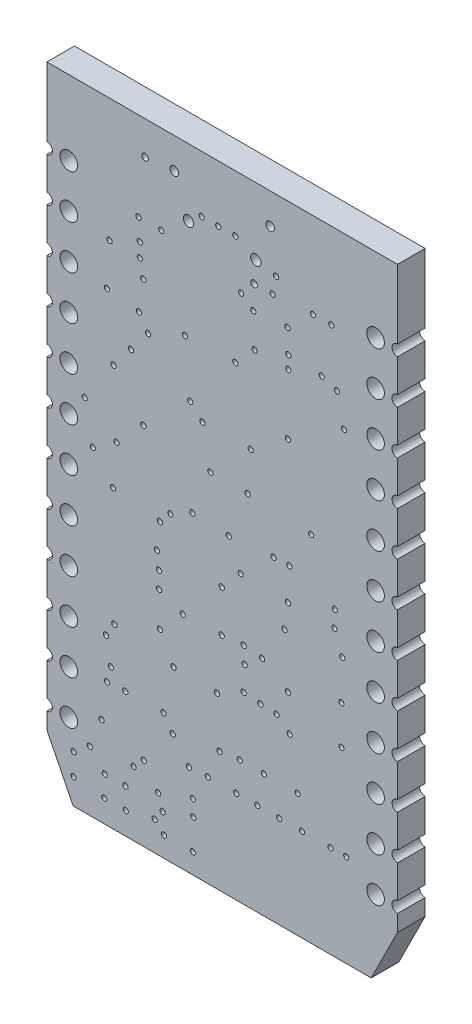
SolidWorks part; units mm, degrees
ref_plane "Front Plane" through (0, 0, 0) normal (0, 0, 1) x (1, 0, 0)
ref_plane "Top Plane" through (0, 0, 0) normal (0, 1, 0) x (1, 0, 0)
ref_plane "Right Plane" through (0, 0, 0) normal (1, 0, 0) x (0, 0, -1)
ref_plane "Dielectric_Layer Layer 1" through (0, 0, 1.6) normal (0, 0, 1) x (1, 0, 0)
sketch "Sketch1" plane through (0, 0, 0) normal (0, 0, 1) x (1, 0, 0)
  line L0 (0, 36.576) -> (0, 3.048)
  line L1 (0, 3.048) -> (1.524, 0)
  line L2 (1.524, 0) -> (18.796, 0)
  line L3 (18.796, 0) -> (20.32, 3.048)
  line L4 (20.32, 3.048) -> (20.32, 36.576)
  line L5 (20.32, 36.576) -> (0, 36.576)
extrude "Board_Outline" add sketch "Sketch1" along normal blind 1.6 separate body
sketch "Sketch2" plane through (0, 0, 0) normal (0, 0, 1) x (1, 0, 0)
  circle A0 centre (12.11, 32.698) radius 0.3
  circle A1 centre (8.21, 32.698) radius 0.3
  circle A2 centre (13.3096, 10.4902) radius 0.1524
  circle A3 centre (17.2212, 26.7462) radius 0.1524
  circle A4 centre (4.8768, 24.5872) radius 0.1524
  circle A5 centre (16.8142, 28.4788) radius 0.1524
  circle A6 centre (9.4742, 20.7264) radius 0.1524
  circle A7 centre (13.9954, 28.1432) radius 0.1524
  circle A8 centre (11.6332, 20.7264) radius 0.1524
  circle A9 centre (10.0076, 6.985) radius 0.1524
  circle A10 centre (13.9954, 28.8798) radius 0.1524
  circle A11 centre (12.0396, 28.1432) radius 0.1524
  circle A12 centre (3.9116, 10.3124) radius 0.1524
  circle A13 centre (5.588, 21.1328) radius 0.1524
  circle A14 centre (3.429, 9.525) radius 0.1524
  circle A15 centre (3.8354, 17.1196) radius 0.1524
  circle A16 centre (11.4046, 10.6426) radius 0.1524
  circle A17 centre (12.3698, 10.541) radius 0.1524
  circle A18 centre (7.874, 12.8016) radius 0.1524
  circle A19 centre (6.5532, 16.7894) radius 0.1524
  circle A20 centre (10.1346, 15.2908) radius 0.1524
  circle A21 centre (11.2268, 16.51) radius 0.1524
  circle A22 centre (14.0462, 18.3134) radius 0.1524
  circle A23 centre (13.1318, 18.288) radius 0.1524
  circle A24 centre (17.1196, 15.2654) radius 0.1524
  circle A25 centre (16.6878, 17.4498) radius 0.1524
  circle A26 centre (9.8552, 9.8298) radius 0.1524
  circle A27 centre (8.4328, 18.161) radius 0.1524
  circle A28 centre (2.4892, 3.4798) radius 0.15
  circle A29 centre (1.5494, 1.4732) radius 0.15
  circle A30 centre (8.4582, 1.1684) radius 0.15
  circle A31 centre (6.2484, 1.7018) radius 0.15
  circle A32 centre (14.5288, 7.1374) radius 0.15
  circle A33 centre (4.5466, 2.5146) radius 0.15
  circle A34 centre (1.5494, 2.7432) radius 0.15
  circle A35 centre (9.3218, 5.3594) radius 0.15
  circle A36 centre (16.4338, 5.3594) radius 0.15
  circle A37 centre (13.462, 5.3594) radius 0.15
  circle A38 centre (10.9728, 5.3594) radius 0.15
  circle A39 centre (12.192, 5.3594) radius 0.15
  circle A40 centre (3.7084, 8.0772) radius 0.15
  circle A41 centre (11.2522, 30.607) radius 0.15
  circle A42 centre (5.3848, 29.4386) radius 0.15
  circle A43 centre (5.3848, 30.2514) radius 0.1524
  circle A44 centre (3.6322, 29.4386) radius 0.1524
  circle A45 centre (8.9662, 33.2994) radius 0.1524
  circle A46 centre (13.2842, 32.4612) radius 0.1524
  circle A47 centre (13.9446, 30.226) radius 0.1524
  circle A48 centre (15.3162, 20.5232) radius 0.15
  circle A49 centre (4.0386, 19.5072) radius 0.15
  circle A50 centre (11.4554, 12.065) radius 0.15
  circle A51 centre (12.4714, 12.8778) radius 0.15
  circle A52 centre (3.4798, 26.9494) radius 0.15
  circle A53 centre (17.0688, 10.7188) radius 0.15
  circle A54 centre (9.017, 23.0124) radius 0.15
  circle A55 centre (17.3482, 5.3594) radius 0.15
  circle A56 centre (3.4798, 7.2136) radius 0.15
  circle A57 centre (14.7828, 5.3594) radius 0.15
  circle A58 centre (3.3528, 2.5146) radius 0.15
  circle A59 centre (11.811, 23.0378) radius 0.15
  circle A60 centre (8.001, 26.8478) radius 0.15
  circle A61 centre (13.97, 24.638) radius 0.15
  circle A62 centre (6.6294, 31.4452) radius 0.15
  circle A63 centre (13.081, 31.4706) radius 0.1524
  circle A64 centre (11.176, 7.1374) radius 0.15
  circle A65 centre (7.1628, 17.4752) radius 0.15
  circle A66 centre (2.1844, 20.828) radius 0.15
  circle A67 centre (17.0688, 12.954) radius 0.15
  circle A68 centre (11.9634, 30.0736) radius 0.15
  circle A69 centre (8.4582, 3.8354) radius 0.15
  circle A70 centre (4.572, 1.2954) radius 0.15
  circle A71 centre (6.7818, 1.1684) radius 0.15
  circle A72 centre (3.3274, 1.2954) radius 0.15
  circle A73 centre (5.0292, 3.7338) radius 0.15
  circle A74 centre (6.7056, 2.3114) radius 0.15
  circle A75 centre (12.573, 7.1374) radius 0.15
  circle A76 centre (8.4836, 2.921) radius 0.15
  circle A77 centre (5.6134, 4.3434) radius 0.15
  circle A78 centre (6.4516, 3.1242) radius 0.15
  circle A79 centre (3.175, 5.1562) radius 0.15
  circle A80 centre (8.2296, 5.3086) radius 0.15
  circle A81 centre (6.7564, 7.2898) radius 0.15
  circle A82 centre (5.334, 26.6954) radius 0.1524
  circle A83 centre (9.9314, 33.2994) radius 0.1524
  circle A84 centre (5.8674, 25.8826) radius 0.1524
  circle A85 centre (10.922, 33.2994) radius 0.1524
  circle A86 centre (5.3086, 31.4452) radius 0.1524
  circle A87 centre (5.588, 28.4734) radius 0.1524
  circle A88 centre (15.4178, 31.623) radius 0.1524
  circle A89 centre (10.922, 26.9494) radius 0.1524
  circle A90 centre (3.8608, 23.2918) radius 0.1524
  circle A91 centre (8.3058, 23.6982) radius 0.1524
  circle A92 centre (4.5466, 7.2644) radius 0.1524
  circle A93 centre (7.3406, 9.8806) radius 0.1524
  circle A94 centre (7.2898, 6.5024) radius 0.1524
  circle A95 centre (6.5532, 11.3792) radius 0.1524
  circle A96 centre (6.3754, 15.2654) radius 0.1524
  circle A97 centre (11.4046, 13.0048) radius 0.1524
  circle A98 centre (16.4846, 31.623) radius 0.1524
  circle A99 centre (6.4968, 14.32) radius 0.1524
  circle A100 centre (10.1346, 12.8778) radius 0.1524
  circle A101 centre (15.9258, 28.7782) radius 0.1524
  circle A102 centre (6.5024, 13.3604) radius 0.1524
  circle A103 centre (2.667, 18.5674) radius 0.1524
  circle A104 centre (13.97, 16.4338) radius 0.1524
  circle A105 centre (10.541, 18.0594) radius 0.1524
  circle A106 centre (5.6896, 34.6456) radius 0.1905
  circle A107 centre (12.0142, 31.4452) radius 0.1905
  circle A108 centre (16.6624, 16.4846) radius 0.1524
  circle A109 centre (14.0716, 9.8806) radius 0.1524
  circle A110 centre (13.97, 11.938) radius 0.1524
  circle A111 centre (13.7668, 14.986) radius 0.1524
extrude "NPTH" cut sketch "Sketch2" along normal through all
sketch "Sketch3" plane through (0, 0, 0) normal (0, 0, 1) x (1, 0, 0)
  circle A0 centre (1.27, 4.32) radius 0.51
  circle A1 centre (1.27, 6.86) radius 0.51
  circle A2 centre (1.27, 9.4) radius 0.51
  circle A3 centre (1.27, 11.94) radius 0.51
  circle A4 centre (1.27, 14.48) radius 0.51
  circle A5 centre (1.27, 17.02) radius 0.51
  circle A6 centre (1.27, 19.56) radius 0.51
  circle A7 centre (1.27, 22.1) radius 0.51
  circle A8 centre (1.27, 24.64) radius 0.51
  circle A9 centre (1.27, 27.18) radius 0.51
  circle A10 centre (1.27, 29.72) radius 0.51
  circle A11 centre (1.27, 32.26) radius 0.51
  circle A12 centre (0, 4.32) radius 0.32
  circle A13 centre (0, 6.86) radius 0.32
  circle A14 centre (0, 9.4) radius 0.32
  circle A15 centre (0, 11.94) radius 0.32
  circle A16 centre (0, 14.48) radius 0.32
  circle A17 centre (0, 17.02) radius 0.32
  circle A18 centre (0, 19.56) radius 0.32
  circle A19 centre (0, 22.1) radius 0.32
  circle A20 centre (0, 24.64) radius 0.32
  circle A21 centre (0, 27.18) radius 0.32
  circle A22 centre (0, 29.72) radius 0.32
  circle A23 centre (0, 32.26) radius 0.32
  circle A24 centre (19.05, 32.26) radius 0.51
  circle A25 centre (19.05, 29.72) radius 0.51
  circle A26 centre (19.05, 27.18) radius 0.51
  circle A27 centre (19.05, 24.64) radius 0.51
  circle A28 centre (19.05, 22.1) radius 0.51
  circle A29 centre (19.05, 19.56) radius 0.51
  circle A30 centre (19.05, 17.02) radius 0.51
  circle A31 centre (19.05, 14.48) radius 0.51
  circle A32 centre (19.05, 11.94) radius 0.51
  circle A33 centre (19.05, 9.4) radius 0.51
  circle A34 centre (19.05, 6.86) radius 0.51
  circle A35 centre (19.05, 4.32) radius 0.51
  circle A36 centre (20.32, 32.26) radius 0.32
  circle A37 centre (20.32, 29.72) radius 0.32
  circle A38 centre (20.32, 27.18) radius 0.32
  circle A39 centre (20.32, 24.64) radius 0.32
  circle A40 centre (20.32, 22.1) radius 0.32
  circle A41 centre (20.32, 19.56) radius 0.32
  circle A42 centre (20.32, 17.02) radius 0.32
  circle A43 centre (20.32, 14.48) radius 0.32
  circle A44 centre (20.32, 11.94) radius 0.32
  circle A45 centre (20.32, 9.4) radius 0.32
  circle A46 centre (20.32, 6.86) radius 0.32
  circle A47 centre (20.32, 4.32) radius 0.32
  circle A48 centre (12.94, 34.8) radius 0.25
  circle A49 centre (7.39, 34.8) radius 0.25
extrude "PTH" cut sketch "Sketch3" along normal through all
